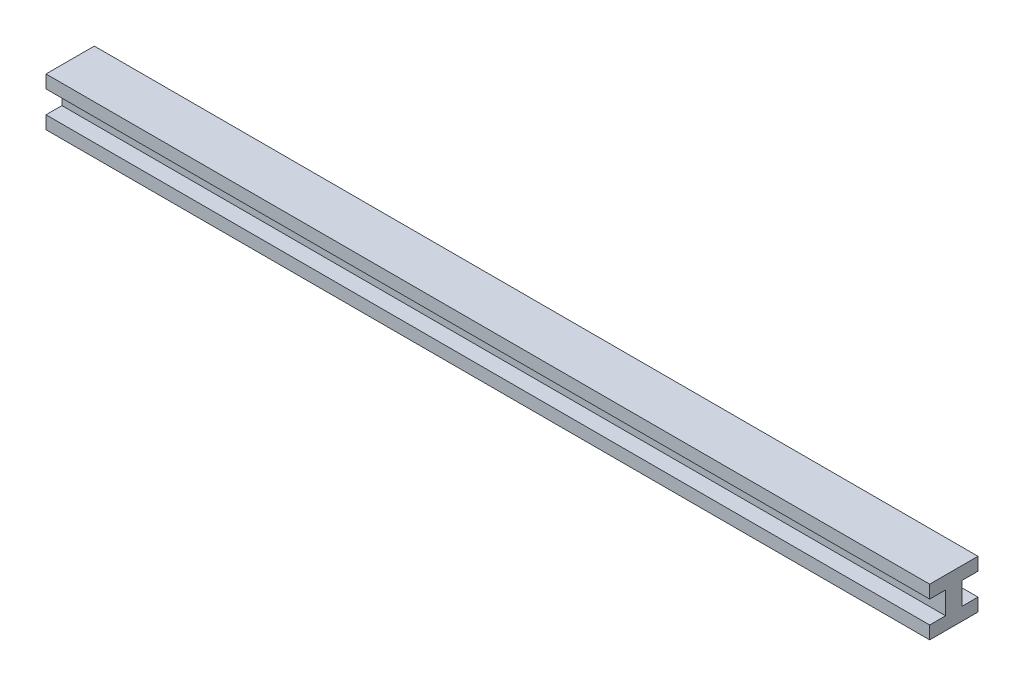
SolidWorks part; units mm, degrees
ref_plane "Front Plane" through (0, 0, 0) normal (0, 0, 1) x (1, 0, 0)
ref_plane "Top Plane" through (0, 0, 0) normal (0, 1, 0) x (1, 0, 0)
ref_plane "Right Plane" through (0, 0, 0) normal (1, 0, 0) x (0, 0, -1)
sketch "Sketch1" plane through (0, 0, 0) normal (1, 0, 0) x (0, 0, -1)
  line L0 (55, -22) -> (82, -22)
  line L1 (0, 0) -> (82, 0)
  line L2 (0, 0) -> (0, -22)
  line L3 (0, -22) -> (27, -22)
  line L4 (82, 0) -> (82, -22)
  line L6 (55, -22) -> (55, -60)
  line L7 (55, -82) -> (27, -82)
  line L8 (27, -22) -> (27, -60)
  line L9 (27, -60) -> (0, -60)
  line L10 (82, -60) -> (55, -60)
  line L11 (82, -60) -> (82, -82)
  line L12 (82, -82) -> (0, -82)
  line L13 (0, -60) -> (0, -82)
  point P9 (41, -82)
  point P10 (41, 0)
  dimension "D1" = 22
  dimension "D2" = 82
  dimension "D4" = 60
  dimension "D5" = 82
  dimension "D3" = 28
  dimension "D6" = 14
extrude "Boss-Extrude1" add sketch "Sketch1" along normal blind 1500 contours L3 L8 L9 L13 L12 L11 L10 L6 L0 L4 L1 L2
equation "\"D6@Sketch1\"=\"D3@Sketch1\"/2"
